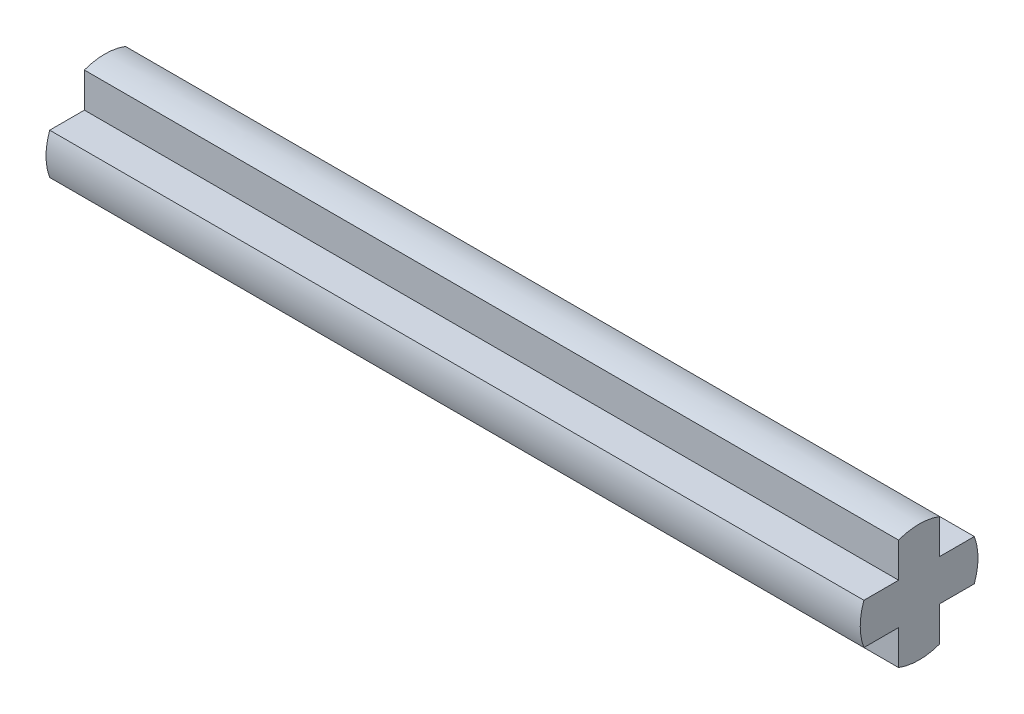
SolidWorks part; units mm, degrees
ref_plane "Front Plane" through (0, 0, 0) normal (0, 0, 1) x (1, 0, 0)
ref_plane "Top Plane" through (0, 0, 0) normal (0, 1, 0) x (1, 0, 0)
ref_plane "Right Plane" through (0, 0, 0) normal (1, 0, 0) x (0, 0, -1)
sketch "Sketch1" plane through (0, 0, 0) normal (1, 0, 0) x (0, 0, -1)
  line L0 (-2.1564, 0.8) -> (-0.8, 0.8)
  line L1 (2.1564, -0.8) -> (-2.1564, -0.8) construction
  line L2 (2.1564, -0.8) -> (2.1564, 0.8) construction
  line L3 (2.1564, 0.8) -> (-2.1564, 0.8) construction
  line L4 (-2.1564, -0.8) -> (-2.1564, 0.8) construction
  line L5 (2.1564, -0.8) -> (-2.1564, 0.8) construction
  line L6 (2.1564, 0.8) -> (-2.1564, -0.8) construction
  line L7 (-0.8, -2.1564) -> (0.8, -2.1564) construction
  line L8 (-0.8, -2.1564) -> (-0.8, 2.1564) construction
  line L9 (-0.8, 2.1564) -> (0.8, 2.1564) construction
  line L10 (0.8, -2.1564) -> (0.8, 2.1564) construction
  line L11 (-0.8, -2.1564) -> (0.8, 2.1564) construction
  line L12 (-0.8, 2.1564) -> (0.8, -2.1564) construction
  line L13 (-0.8, 0.8) -> (-0.8, 2.1564)
  line L14 (0.8, 2.1564) -> (0.8, 0.8)
  line L15 (0.8, 0.8) -> (2.1564, 0.8)
  line L16 (2.1564, -0.8) -> (0.8, -0.8)
  line L17 (0.8, -0.8) -> (0.8, -2.1564)
  line L18 (-0.8, -2.1564) -> (-0.8, -0.8)
  line L19 (-0.8, -0.8) -> (-2.1564, -0.8)
  circle A0 centre (0, 0) radius 2.3 construction
  spline S0 degree 2 poles (-2.1564, -0.8) (-2.4436, 0) (-2.1564, 0.8) knots 0 0 0 1 1 1
  spline S1 degree 2 poles (-0.8, 2.1564) (0, 2.4436) (0.8, 2.1564) knots 0 0 0 1 1 1
  spline S2 degree 2 poles (2.1564, 0.8) (2.4436, 0) (2.1564, -0.8) knots 0 0 0 1 1 1
  spline S3 degree 2 poles (0.8, -2.1564) (0, -2.4436) (-0.8, -2.1564) knots 0 0 0 1 1 1
  point P18 (0, 0)
  dimension "D1" = 4.6
  dimension "D2" = 1.6
  dimension "D3" = 1.6
extrude "Boss-Extrude1" add sketch "Sketch1" along normal blind 31.8
